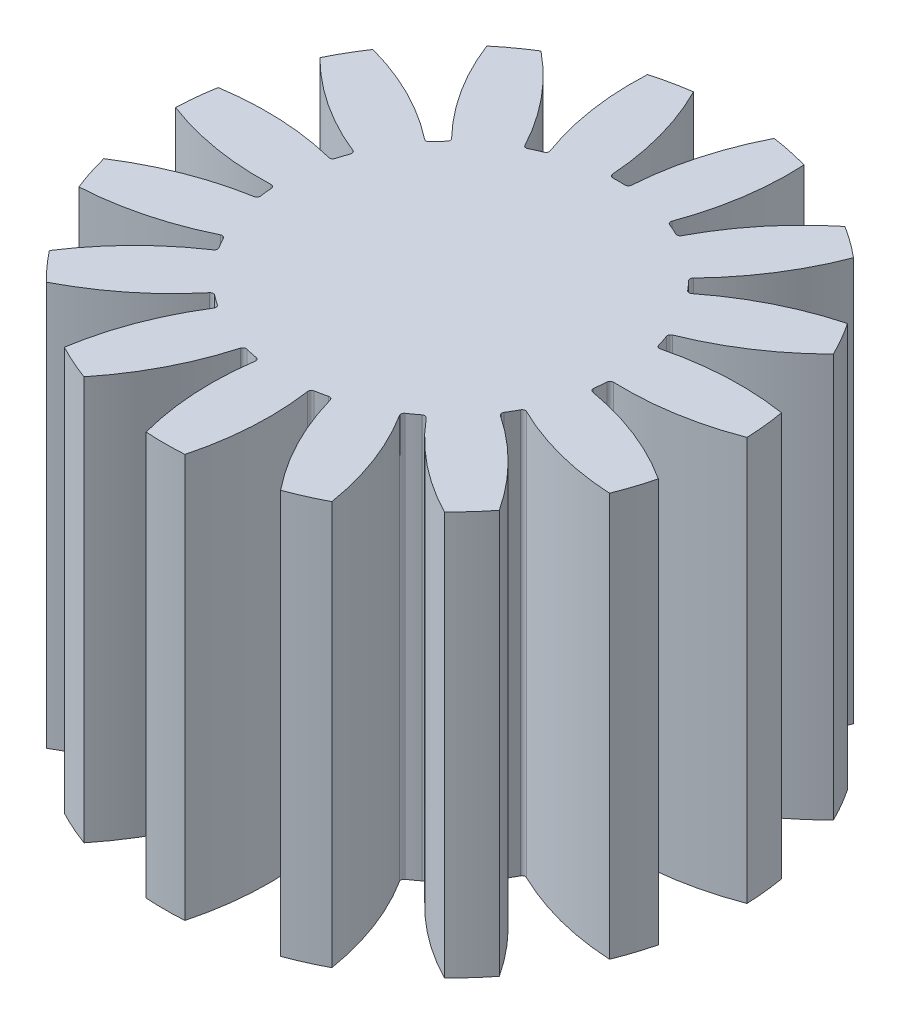
SolidWorks part; units mm, degrees
ref_plane "Спереди" through (0, 0, 0) normal (0, 0, 1) x (1, 0, 0)
ref_plane "Сверху" through (0, 0, 0) normal (0, 1, 0) x (1, 0, 0)
ref_plane "Справа" through (0, 0, 0) normal (1, 0, 0) x (0, 0, -1)
sketch "Эскиз1" plane through (0, 0, 0) normal (0, 1, 0) x (1, 0, 0)
  circle A0 centre (0, 0) radius 8.5
  circle A1 centre (0, 0) radius 7.5 construction
  circle A2 centre (0, 0) radius 6.25 construction
  dimension "D2" = 15
  dimension "D1" = 17
  dimension "D3" = 2.25
extrude "Бобышка-Вытянуть1" add sketch "Эскиз1" along normal blind 12
sketch "Эскиз2" plane through (0, 12, 0) normal (0, 1, 0) x (1, 0, 0)
  circle A0 centre (0, 0) radius 5
  circle A1 centre (0, 0) radius 7.5
sketch "Эскиз3" plane through (0, 12, 0) normal (0, 1, 0) x (1, 0, 0)
  line L0 (0, 0) -> (0, 10.3795) construction
  line L1 (0, 0) -> (-0.2779, 4.9923) construction
  line L2 (-0.784, 7.4589) -> (0.784, 7.4589) construction
  line L3 (0.784, 7.4589) -> (2.3176, 7.1329) construction
  line L4 (-2.5079, 12.1953) -> (0.9399, 2.7226) construction
  line L5 (0, 0) -> (3.2169, 15.1344) construction
  arc A0 (-1.7433, 9.3387) -> (-0.2779, 4.9923) centre (-8.8762, 4.5136) cw
  arc A1 (1.7433, 9.3387) -> (0.2779, 4.9923) centre (8.8762, 4.5136) ccw
  circle A2 centre (0, 0) radius 5 construction
  arc A3 (0.2779, 4.9923) -> (-0.2779, 4.9923) centre (0, 0) ccw
  circle A4 centre (0, 0) radius 7.5 construction
  circle A6 centre (0, 0) radius 9.5
  arc A7 (1.7433, 9.3387) -> (-1.7433, 9.3387) centre (0, 0) ccw
  point P18 (-0.784, 7.4589)
  dimension "D2" = 20
  dimension "D3" = 12
  dimension "D1" = 1
extrude "Вырез-Вытянуть1" cut sketch "Эскиз3" against normal through all contours A7 A0 A3 A1
fillet "Скругление1" radius 0.1 2 edges at (0.2779, 6, -4.9923) (-0.2779, 6, -4.9923)
pattern_circular "Круговой массив3" count 15 over 360 about axis through (0, 0, 0) along (0, 1, 0) of "Скругление1", "Вырез-Вытянуть1"
equation "\"модуль\" = 1"
equation "\"число зубьев\"= 15"
equation "\"D2@Эскиз1\"=\"модуль\"*\"число зубьев\""
equation "\"D1@Эскиз1\"=\"модуль\"*(\"число зубьев\"+2)"
equation "\"D3@Эскиз3\"=180/\"число зубьев\""
equation "\"D1@Скругление1\"=\"модуль\"*0.1"
